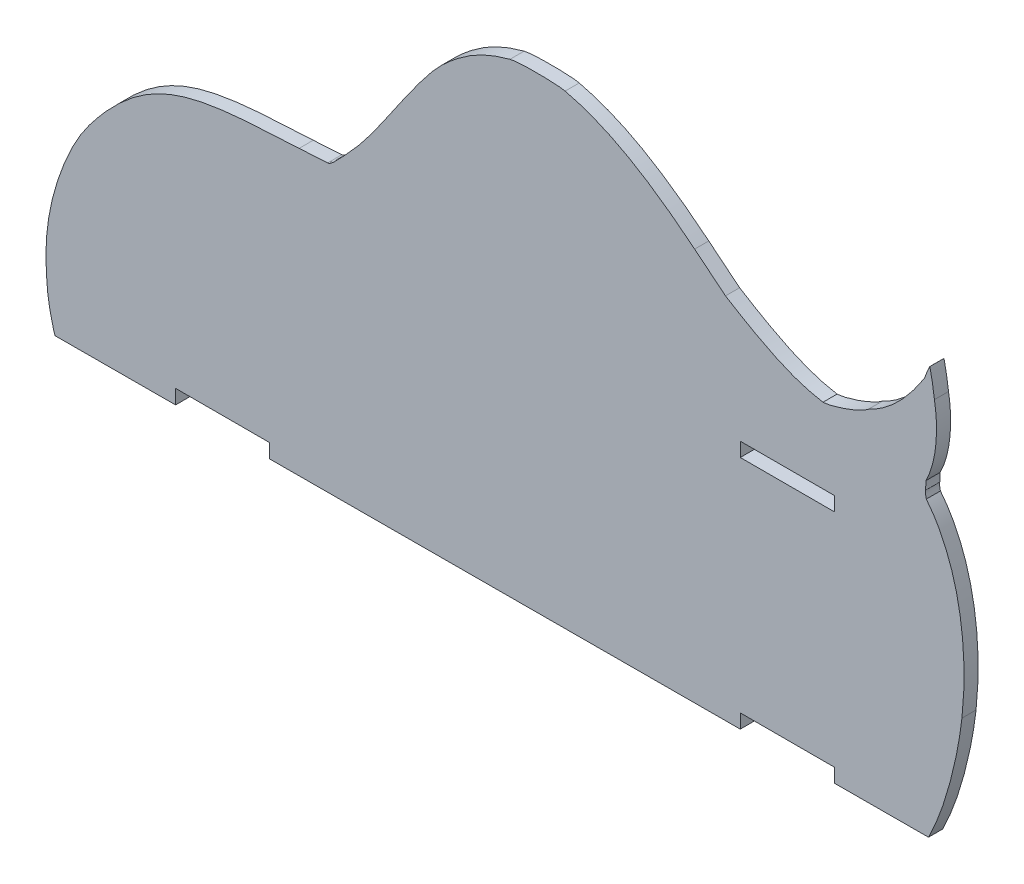
SolidWorks part; units mm, degrees
ref_plane "Front Plane" through (0, 0, 0) normal (0, 0, 1) x (1, 0, 0)
ref_plane "Top Plane" through (0, 0, 0) normal (0, 1, 0) x (1, 0, 0)
ref_plane "Right Plane" through (0, 0, 0) normal (1, 0, 0) x (0, 0, -1)
sketch "Sketch1" plane through (0, 0, 0) normal (0, 0, 1) x (1, 0, 0)
  line L0 (221.359, 265.2868) -> (201.359, 265.2868)
  line L1 (201.359, 265.2868) -> (201.359, 262.2868)
  line L2 (201.359, 262.2868) -> (221.359, 262.2868)
  line L3 (221.359, 262.2868) -> (221.359, 265.2868)
  line L4 (116.6252, 269.6265) -> (210.2723, 269.6265)
  line L5 (210.2723, 269.6265) -> (201.8432, 279.7414)
  line L6 (55.7716, 211.885) -> (81.3596, 211.9556)
  line L7 (81.3596, 215.0108) -> (81.3596, 211.9556)
  line L8 (101.3596, 215.0108) -> (81.3596, 215.0108)
  line L9 (101.3596, 212.0108) -> (101.3596, 215.0108)
  line L10 (101.3596, 212.0108) -> (201.359, 212.2868)
  line L11 (201.359, 215.2868) -> (201.359, 212.2868)
  line L12 (221.359, 215.2868) -> (201.359, 215.2868)
  line L13 (221.359, 212.342) -> (221.359, 215.2868)
  line L14 (221.359, 212.342) -> (241.359, 212.3972)
  line L15 (122.3954, 271.6265) -> (206.0022, 271.6265)
  line L16 (206.0022, 271.6265) -> (200.3985, 278.3509)
  spline S0 degree 3 poles (201.8432, 279.7414) (201.5234, 280.0294) (200.9013, 280.5936) (199.5436, 281.8463) (197.7214, 283.5497) (195.3337, 285.7777) (191.9193, 288.908) (187.2649, 292.9814) (181.2103, 297.6755) (174.8164, 301.7288) (168.1877, 304.6861) (162.5301, 305.8169) (157.9845, 305.6143) (153.531, 304.5555) (148.3751, 301.8806) (142.7053, 297.2408) (137.4618, 291.7445) (132.5974, 285.9422) (128.8506, 281.3143) (126.0481, 278.0238) (124.0525, 275.8365) (122.4907, 274.3131) (121.5374, 273.4982) (121.1117, 273.1611) (120.7897, 272.9077) (119.9316, 272.2313) (118.5105, 271.112) (117.2542, 270.1221) (116.6252, 269.6265) knots -0.001903 -0.001903 -0.001903 -0.001903 0.015022 0.031947 0.065797 0.099648 0.133498 0.201198 0.268899 0.3366 0.4043 0.472001 0.505851 0.539701 0.607402 0.675102 0.742803 0.810503 0.878204 0.912054 0.945905 0.979755 0.99668 1.000911 1.005143 1.013605 1.047455 1.081306 1.081306 1.081306 1.081306
  spline S1 degree 3 poles (218.9348, 281.2445) (213.1421, 282.1994) (207.621, 284.6538) (198.2179, 290.4543) knots 0 0 0 0 1 1 1 1
  spline S2 degree 3 poles (198.2179, 290.4543) (196.1734, 292.1185) (193.2247, 294.5195) (191.6654, 295.7898) knots 0 0 0 0 1 1 1 1
  spline S3 degree 3 poles (191.6654, 295.7898) (181.1234, 304.3777) (172.6488, 309.0903) (164.132, 311.1005) knots 0 0 0 0 1 1 1 1
  spline S4 degree 3 poles (164.132, 311.1005) (162.0755, 311.5859) (154.2822, 311.5832) (152.4129, 311.0969) knots 0 0 0 0 1 1 1 1
  spline S5 degree 3 poles (152.4129, 311.0969) (146.792, 309.6333) (142.5046, 307.167) (137.902, 302.7496) knots 0 0 0 0 1 1 1 1
  spline S6 degree 3 poles (137.902, 302.7496) (135.5531, 300.4952) (132.3709, 296.2739) (126.3917, 287.4803) knots 0 0 0 0 1 1 1 1
  spline S7 degree 3 poles (126.3917, 287.4803) (122.6489, 281.9759) (120.6119, 279.3752) (117.2016, 275.747) knots 0 0 0 0 1 1 1 1
  spline S8 degree 3 poles (117.2016, 275.747) (114.7799, 273.1706) (114.2745, 272.7283) (113.6733, 272.6591) knots 0 0 0 0 1 1 1 1
  spline S9 degree 3 poles (113.6733, 272.6591) (113.2873, 272.6145) (110.5594, 272.4545) (107.6112, 272.3033) knots 0 0 0 0 1 1 1 1
  spline S10 degree 3 poles (107.6112, 272.3033) (86.3468, 271.2128) (75.9191, 271.2271) (63.0082, 254.2734) knots 0 0 0 0 1 1 1 1
  spline S11 degree 3 poles (63.0082, 254.2734) (58.7967, 248.7432) (54.6457, 238.6663) (53.9302, 229.1289) knots 0 0 0 0 1 1 1 1
  spline S12 degree 3 poles (53.9302, 229.1289) (53.7211, 226.3424) (53.7926, 222.2266) (54.1879, 218.9296) knots 0 0 0 0 1 1 1 1
  spline S13 degree 3 poles (54.1879, 218.9296) (54.4906, 216.404) (55.3302, 212.7484) (55.7716, 211.885) knots 0 0 0 0 1 1 1 1
  spline S14 degree 3 poles (241.359, 212.3972) (244.6293, 218.7488) (247.4086, 228.7099) (248.4674, 237.8739) knots 0 0 0 0 1 1 1 1
  spline S15 degree 3 poles (248.4674, 237.8739) (250.0795, 252.8878) (247.215, 266.6974) (240.8914, 274.3981) knots 0 0 0 0 1 1 1 1
  spline S16 degree 3 poles (240.8914, 274.3981) (240.6985, 275.2736) (240.6431, 275.9819) (240.7681, 275.9721) knots 0 0 0 0 1 1 1 1
  spline S17 degree 3 poles (240.7681, 275.9721) (240.7489, 276.096) (240.7693, 276.9013) (240.8134, 277.7615) knots 0 0 0 0 1 1 1 1
  spline S18 degree 3 poles (240.8134, 277.7615) (242.9271, 281.8425) (243.6013, 287.7458) (242.618, 293.5612) knots 0 0 0 0 1 1 1 1
  spline S19 degree 3 poles (242.618, 293.5612) (242.4156, 295.3604) (241.7535, 299.0766) (241.6231, 299.1457) knots 0 0 0 0 1 1 1 1
  spline S20 degree 3 poles (241.6231, 299.1457) (241.5786, 299.1917) (241.0597, 297.9488) (240.4698, 296.3838) knots 0 0 0 0 1 1 1 1
  spline S21 degree 3 poles (240.4698, 296.3838) (236.6511, 290.4798) (232.9289, 286.8413) (228.6321, 284.8126) knots 0 0 0 0 1 1 1 1
  spline S22 degree 3 poles (228.6321, 284.8126) (226.8611, 283.3997) (221.392, 281.3873) (218.9348, 281.2445) knots 0 0 0 0 1 1 1 1
  spline S23 degree 3 poles (200.3985, 278.3509) (190.8675, 286.9321) (155.7555, 324.2523) (131.4813, 278.785) (122.3954, 271.6265) knots 0 0 0 0 0.511041 1 1 1 1
  dimension "D1" = 185.5874
extrude "Boss-Extrude1" add sketch "Sketch1" along normal blind 3 contours L16 S23 L15 | S21 S22 S1 S2 S3 S4 S5 S6 S7 S8 S9 S10 S11 S12 S13 L6 L7 L8 L9 L10 L11 L12 L13 L14 S14 S15 S16 S17 S18 S19 S20 L3 L2 L1 L0 S0 L5 L4 | L5 S0 L4 S23 L16 L15
